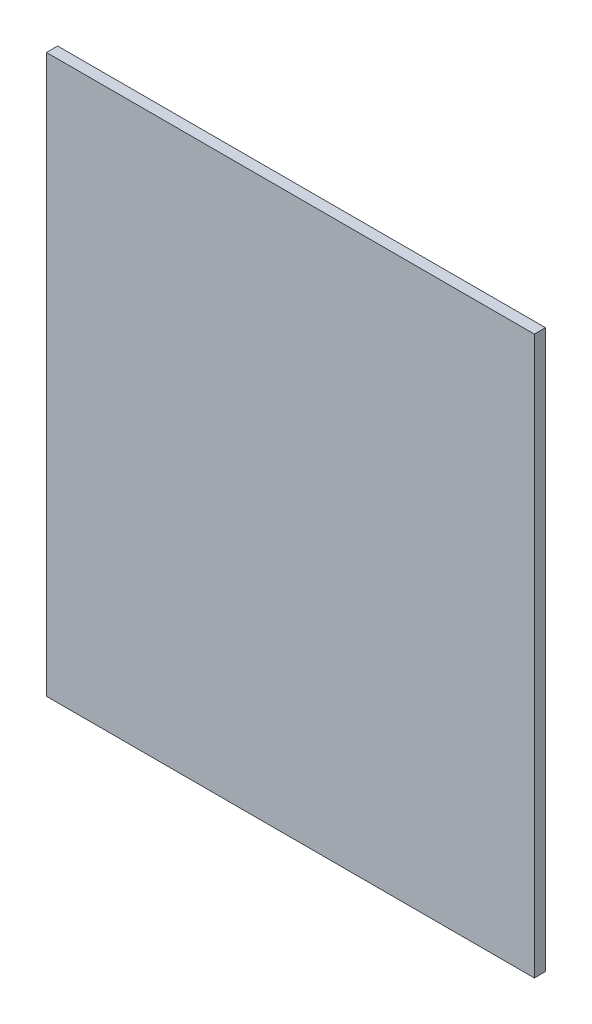
SolidWorks part; units mm, degrees
ref_plane "Спереди" through (0, 0, 0) normal (0, 0, 1) x (1, 0, 0)
ref_plane "Сверху" through (0, 0, 0) normal (0, 1, 0) x (1, 0, 0)
ref_plane "Справа" through (0, 0, 0) normal (1, 0, 0) x (0, 0, -1)
sketch "Эскиз1" plane through (0, 0, 0) normal (0, 0, 1) x (1, 0, 0)
  line L1 (-37.6628, 43.5807) -> (662.3372, 43.5807)
  line L2 (-37.6628, 43.5807) -> (-37.6628, -756.4193)
  line L3 (-37.6628, -756.4193) -> (662.3372, -756.4193)
  line L4 (662.3372, 43.5807) -> (662.3372, -756.4193)
  dimension "D1" = 700
  dimension "D2" = 800
extrude "Бобышка-Вытянуть1" add sketch "Эскиз1" along normal blind 16
